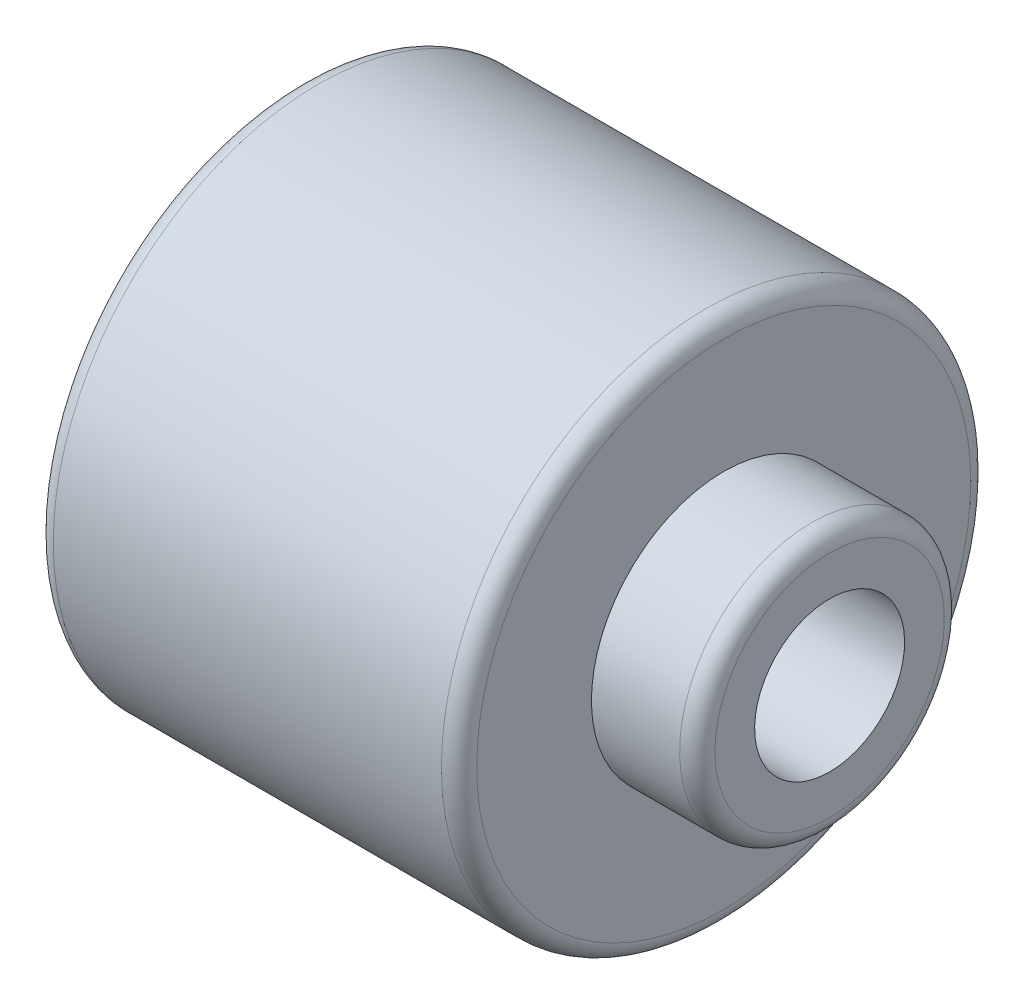
SolidWorks part; units mm, degrees
ref_plane "Ön Düzlem" through (0, 0, 0) normal (0, 0, 1) x (1, 0, 0)
ref_plane "Üst Düzlem" through (0, 0, 0) normal (0, 1, 0) x (1, 0, 0)
ref_plane "Sağ Düzlem" through (0, 0, 0) normal (1, 0, 0) x (0, 0, -1)
sketch "Çizim1" plane through (0, 0, 0) normal (0, 0, 1) x (1, 0, 0)
  line L0 (0, 0) -> (0, 15)
  line L1 (0, 15) -> (24, 15)
  line L2 (24, 15) -> (24, 7.5)
  line L3 (24, 7.5) -> (30, 7.5)
  line L4 (30, 7.5) -> (30, 0)
  line L5 (30, 0) -> (0, 0) construction
  line L6 (0, 0) -> (30, 0)
  dimension "D1" = 15
  dimension "D2" = 7.5
  dimension "D3" = 6
  dimension "D4" = 30
revolve "Döndür1" add sketch "Çizim1" angle 360 about L5
sketch "Çizim2" plane through (0, 0, 0) normal (-1, 0, 0) x (0, 0, 1)
  circle A0 centre (0, 0) radius 4.25
  dimension "D1" = 8.5
extrude "Kes-Ekstrüzyon1" cut sketch "Çizim2" against normal blind 30
cosmetic thread "Kozmetik Diş Açma1" parameters "D2"=10
fillet "Radyus1" radius 1 3 edges at (0, 15, 0) (24, 15, 0) (30, 7.5, 0)
